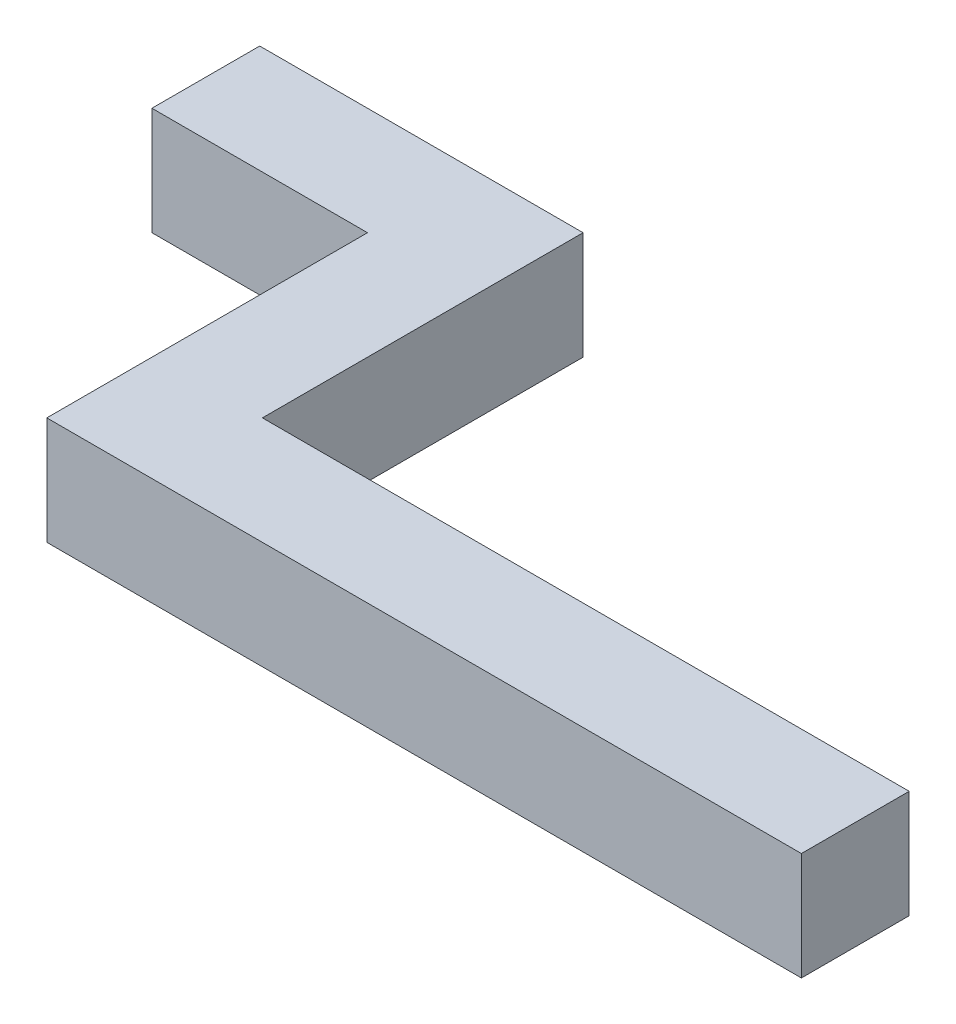
SolidWorks part; units mm, degrees
ref_plane "Front Plane" through (0, 0, 0) normal (0, 0, 1) x (1, 0, 0)
ref_plane "Top Plane" through (0, 0, 0) normal (0, 1, 0) x (1, 0, 0)
ref_plane "Right Plane" through (0, 0, 0) normal (1, 0, 0) x (0, 0, -1)
sketch "Sketch1" plane through (0, 0, 0) normal (0, 1, 0) x (1, 0, 0)
  line L0 (0, 0) -> (60, 0)
  line L1 (0, 0) -> (0, -20)
  line L2 (60, 0) -> (60, -59.5)
  line L3 (0, -20) -> (40, -20)
  line L5 (40, -20) -> (40, -79.5)
  line L7 (40, -79.5) -> (126.9375, -79.5)
  line L8 (126.9375, -79.5) -> (180, -79.5)
  line L10 (180, -79.5) -> (180, -59.5)
  line L11 (60, -59.5) -> (180, -59.5)
  point P0 (350.7574, -120.3477)
  dimension "D1" = 60
  dimension "D4" = 20
  dimension "D5" = 59.5
  dimension "D6" = 20
  dimension "D7" = 120
extrude "Boss-Extrude1" add sketch "Sketch1" along normal blind 20
